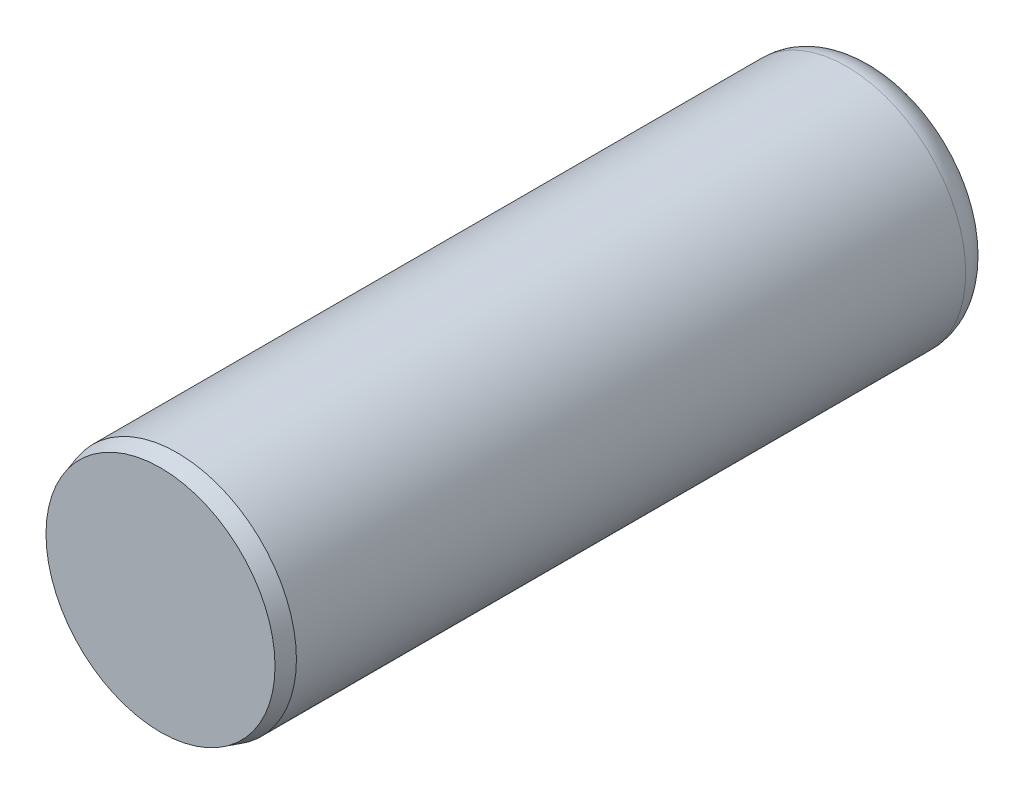
SolidWorks part; units mm, degrees
ref_plane "Front Plane" through (0, 0, 0) normal (0, 0, 1) x (1, 0, 0)
ref_plane "Top Plane" through (0, 0, 0) normal (0, 1, 0) x (1, 0, 0)
ref_plane "Right Plane" through (0, 0, 0) normal (1, 0, 0) x (0, 0, -1)
sketch "Sketch1" plane through (0, 0, 0) normal (0, 0, 1) x (1, 0, 0)
  circle A0 centre (0, 0) radius 12.7
  point P3 (0, 12.7)
  dimension "Diameter" = 25.4
sketch "Sketch2" plane through (0, 0, 0) normal (1, 0, 0) x (0, 0, -1)
  line L0 (-38.1, 0) -> (38.1, 0) construction
  line L1 (-38.1, 0) -> (-38.1, 12.7)
  line L2 (-38.1, 12.192) -> (-36.3284, 12.7)
  line L3 (-38.1, 12.7) -> (38.1, 12.7)
  line L4 (38.1, 12.7) -> (38.1, 0)
  arc A0 (38.1, 9.525) -> (34.925, 12.7) centre (34.925, 9.525) ccw
  point P11 (29.6418, 12.7)
  dimension "Crown Radius" = 3.175
  dimension "Length" = 76.2
  dimension "Point Diameter" = 24.384
  dimension "Chamfer Angle" = 16
  dimension "Crown Height" = 8.4582
sketch "Sketch3" plane through (0, 0, 0) normal (1, 0, 0) x (0, 0, -1)
  line L0 (38.1, 12.7) -> (38.1, 0) construction
  line L1 (-38.1, 12.7) -> (38.1, 12.7) construction
  line L2 (-38.1, 0) -> (-38.1, 12.7) construction
  line L3 (38.1, 9.525) -> (38.1, 0)
  line L4 (-36.3284, 12.7) -> (34.925, 12.7)
  line L5 (-38.1, 0) -> (-38.1, 12.192)
  line L6 (-38.1, 0) -> (38.1, 0) construction
  line L7 (-38.1, 0) -> (38.1, 0)
  line L8 (-38.1, 12.192) -> (-36.3284, 12.7) construction
  line L9 (-38.1, 12.192) -> (-36.3284, 12.7)
  arc A0 (38.1, 9.525) -> (34.925, 12.7) centre (34.925, 9.525) ccw construction
  arc A1 (38.1, 9.525) -> (34.925, 12.7) centre (34.925, 9.525) ccw
revolve "Revolve1" add sketch "Sketch3" angle 360 about L0
